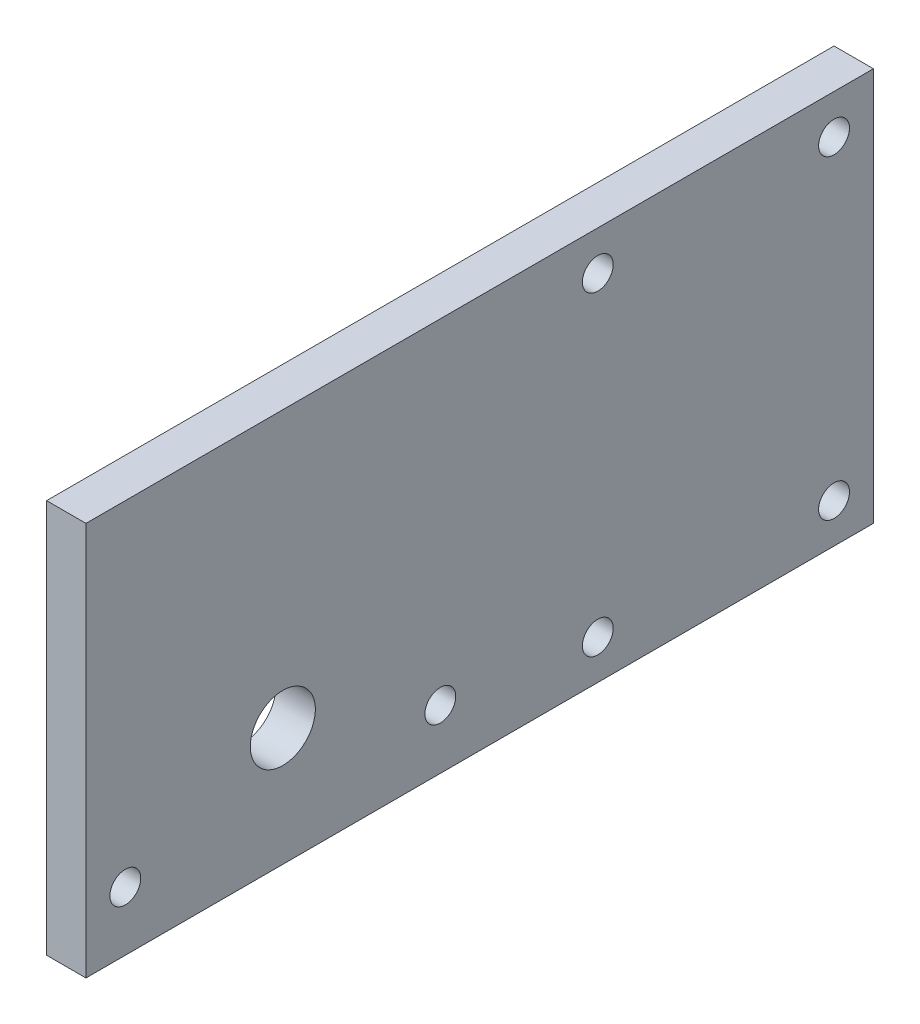
SolidWorks part; units mm, degrees
ref_plane "Front" through (0, 0, 0) normal (0, 0, 1) x (1, 0, 0)
ref_plane "Top" through (0, 0, 0) normal (0, 1, 0) x (1, 0, 0)
ref_plane "Right" through (0, 0, 0) normal (1, 0, 0) x (0, 0, -1)
sketch "Sketch1" plane through (0, 0, 0) normal (1, 0, 0) x (0, 0, -1)
  line L1 (-63.5, -31.75) -> (63.5, -31.75)
  line L2 (-63.5, -31.75) -> (-63.5, 31.75)
  line L3 (-63.5, 31.75) -> (63.5, 31.75)
  line L4 (63.5, -31.75) -> (63.5, 31.75)
  line L5 (-63.5, -31.75) -> (63.5, 31.75) construction
  line L6 (-63.5, 31.75) -> (63.5, -31.75) construction
  point P0 (0, 0)
  dimension "D1" = 127
  dimension "D2" = 63.5
extrude "Boss-Extrude1" add sketch "Sketch1" along normal blind 6.35
hole_wizard "#9 (0.196) Diameter Hole1" positions "Sketch3" profile "Sketch2" hole size "#9" standard "ANSI Inch"
sketch "Sketch3" plane through (0, 0, 0) normal (-1, 0, 0) x (0, 0, 1)
  line L0 (63.5, -31.75) -> (-63.5, -31.75) construction
  line L1 (63.5, 31.75) -> (63.5, -31.75) construction
  point P0 (57.15, -22.225)
  point P2 (6.35, -22.225)
  dimension "D1" = 9.525
  dimension "D2" = 0
  dimension "D3" = 50.8
  dimension "D4" = 6.35
sketch "Sketch2" plane through (0, -22.225, 57.15) normal (0, 1, 0) x (0, 0, 1)
  line L0 (0, 0) -> (0, 71.5997)
  line L1 (0, 71.5997) -> (2.4892, 70.104)
  line L2 (2.4892, 70.104) -> (2.4892, 0)
  line L5 (2.4892, 0) -> (0, 0)
  line L10 (0, 71.5997) -> (-2.4892, 70.104) construction
  line L11 (0, -6.35) -> (0, 107.95) construction
  dimension "Hole Dia." = 4.9784
  dimension "Hole Depth" = 70.104
  dimension "Drill Angle" = 118
hole_wizard "#9 (0.196) Diameter Hole2" positions "Sketch5" profile "Sketch4" hole size "#9" standard "ANSI Inch"
sketch "Sketch5" plane through (0, 0, 0) normal (-1, 0, 0) x (0, 0, 1)
  line L0 (63.5, -31.75) -> (-63.5, -31.75) construction
  line L1 (-63.5, -31.75) -> (-63.5, 31.75) construction
  point P0 (-57.15, -25.4)
  point P2 (-19.05, -25.4)
  point P4 (-19.05, 25.4)
  point P6 (-57.15, 25.4)
  dimension "D1" = 6.35
  dimension "D2" = 6.35
  dimension "D3" = 0
  dimension "D4" = 50.8
  dimension "D5" = 38.1
  dimension "D6" = 50.8
  dimension "D7" = 38.1
  dimension "D8" = 0
sketch "Sketch4" plane through (0, -25.4, -57.15) normal (0, 1, 0) x (0, 0, 1)
  line L0 (0, 0) -> (0, 71.5997)
  line L1 (0, 71.5997) -> (2.4892, 70.104)
  line L2 (2.4892, 70.104) -> (2.4892, 0)
  line L5 (2.4892, 0) -> (0, 0)
  line L10 (0, 71.5997) -> (-2.4892, 70.104) construction
  line L11 (0, -6.35) -> (0, 107.95) construction
  dimension "Hole Dia." = 4.9784
  dimension "Hole Depth" = 70.104
  dimension "Drill Angle" = 118
hole_wizard "Z (0.413) Diameter Hole1" positions "Sketch7" profile "Sketch6" hole size "Z" standard "ANSI Inch"
sketch "Sketch7" plane through (0, 0, 0) normal (-1, 0, 0) x (0, 0, 1)
  line L0 (63.5, -31.75) -> (-63.5, -31.75) construction
  circle A0 centre (6.35, -22.225) radius 2.4892 construction
  point P0 (31.75, -12.7)
  dimension "D2" = 25.4
  dimension "D1" = 19.05
sketch "Sketch6" plane through (0, -12.7, 31.75) normal (0, 1, 0) x (0, 0, 1)
  line L0 (0, 0) -> (0, 73.2556)
  line L1 (0, 73.2556) -> (5.2451, 70.104)
  line L2 (5.2451, 70.104) -> (5.2451, 0)
  line L5 (5.2451, 0) -> (0, 0)
  line L10 (0, 73.2556) -> (-5.2451, 70.104) construction
  line L11 (0, -6.35) -> (0, 107.95) construction
  dimension "Hole Dia." = 10.4902
  dimension "Hole Depth" = 70.104
  dimension "Drill Angle" = 118
